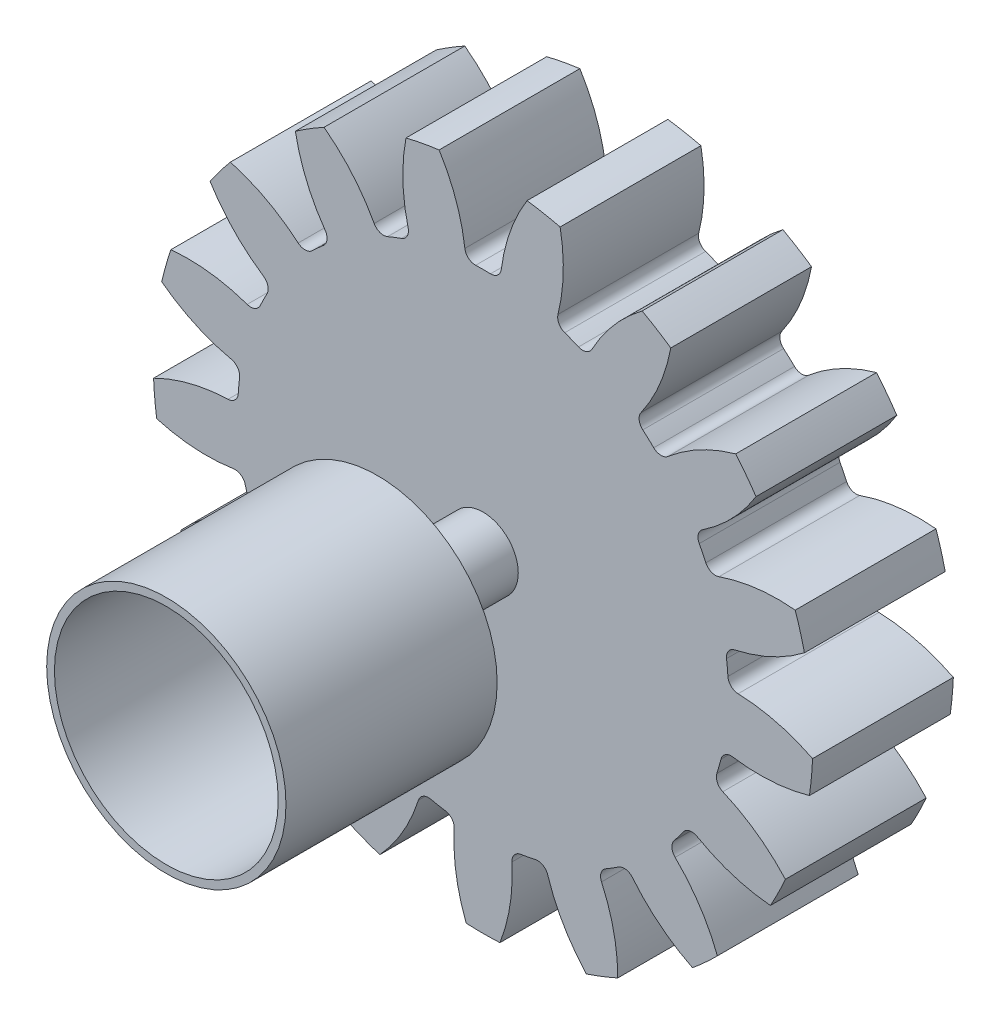
SolidWorks part; units mm, degrees
ref_plane "Front Plane" through (0, 0, 0) normal (0, 0, 1) x (1, 0, 0)
ref_plane "Top Plane" through (0, 0, 0) normal (0, 1, 0) x (1, 0, 0)
ref_plane "Right Plane" through (0, 0, 0) normal (1, 0, 0) x (0, 0, -1)
sketch "Sketch1" plane through (0, 0, 0) normal (0, 0, 1) x (1, 0, 0)
  circle A0 centre (0, 0) radius 4.185 construction
  circle A1 centre (0, 0) radius 4.685
  dimension "D1" = 8.37
  dimension "D2" = 9.37
extrude "Boss-Extrude1" add sketch "Sketch1" along normal mid plane 2
sketch "Sketch3" plane through (0, 0, 0) normal (0, 0, 1) x (1, 0, 0)
  line L0 (0, 4.685) -> (0, 0) construction
  line L1 (0, 0) -> (1.7175, 4.3588) construction
  line L2 (0, 0) -> (0.8741, 4.6027) construction
  line L3 (-0.2452, 3.4764) -> (0, 0) construction
  line L4 (-0.3921, 4.1666) -> (0.3921, 4.1666) construction
  line L5 (0.3921, 4.1666) -> (1.1626, 4.0203) construction
  line L6 (-0.5682, 4.6504) -> (0, 3.0892) construction
  circle A0 centre (0, 0) radius 3.685 construction
  arc A1 (0.2452, 3.4764) -> (-0.2452, 3.4764) centre (0, 0) ccw
  circle A2 centre (0, 0) radius 4.685 construction
  arc A3 (-0.6245, 4.6432) -> (-0.2452, 3.4764) centre (-2.7796, 3.2976) cw
  circle A5 centre (0, 0) radius 4.685 construction
  arc A6 (0.6245, 4.6432) -> (0.2452, 3.4764) centre (2.7796, 3.2976) ccw
  circle A7 centre (0, 0) radius 4.185 construction
  arc A9 (0.6245, 4.6432) -> (-0.6245, 4.6432) centre (0, 0) ccw
  dimension "D1" = 21.505
  dimension "D2" = 1
  dimension "D3" = 1.2
  dimension "D4" = 0.2
  dimension "D5" = 20
extrude "Cut-Extrude1" cut sketch "Sketch3" against normal through all both and the other way through all
fillet "Fillet1" radius 0.15 2 edges at (-0.2452, 3.4764, 0) (0.2452, 3.4764, 0)
pattern_circular "CirPattern1" count 17 over 360 about axis through (0, 0, 0) along (0, 0, 1) of "Fillet1", "Cut-Extrude1"
sketch "Sketch4" plane through (0, 0, 1) normal (0, 0, 1) x (1, 0, 0)
  circle A0 centre (0, 0) radius 0.5
  dimension "D1" = 1
extrude "Boss-Extrude2" add sketch "Sketch4" along normal blind 1.5
sketch "Sketch5" plane through (0, 0, 2.5) normal (0, 0, 1) x (1, 0, 0)
  circle A0 centre (0, 0) radius 1.7
  dimension "D1" = 3.4
extrude "Boss-Extrude3" add sketch "Sketch5" along normal blind 3
sketch "Sketch6" plane through (0, 0, 5.5) normal (0, 0, 1) x (1, 0, 0)
  circle A0 centre (0, 0) radius 1.59
extrude "Cut-Extrude2" cut sketch "Sketch6" against normal blind 2.5
equation "\"module\"= 0.5mm"
equation "\"number of teeth\"= 16.74"
equation "\"pressure angle\"= 20"
equation "\"D1@Sketch1\"= \"module\" * \"number of teeth\""
equation "\"D2@Sketch1\"=(\"number of teeth\" + 2) * \"module\" "
equation "\"D1@Sketch3\"=360 / \"number of teeth\""
equation "\"D3@Sketch3\"= \"module\"  * if( \"module\" => 1.25,2.25,2.4)"
equation "\"D5@Sketch3\"=\"pressure angle\""
equation "\"D1@Fillet1\"=0.3 * \"module\""
equation "\"D1@CirPattern1\"=\"number of teeth\""
equation "\"D1@Chamfer1\"=\"module\""
